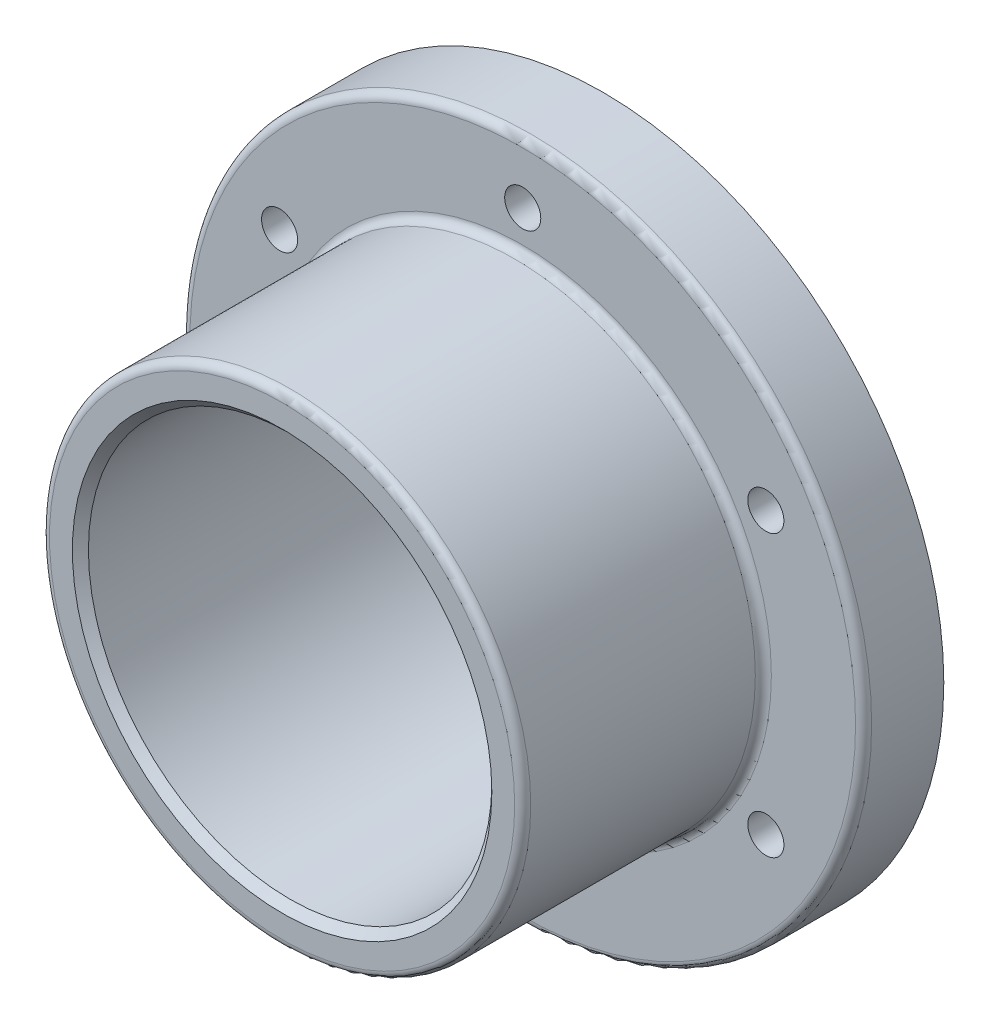
SolidWorks part; units mm, degrees
ref_plane "Front Plane" through (0, 0, 0) normal (0, 0, 1) x (1, 0, 0)
ref_plane "Top Plane" through (0, 0, 0) normal (0, 1, 0) x (1, 0, 0)
ref_plane "Right Plane" through (0, 0, 0) normal (1, 0, 0) x (0, 0, -1)
sketch "Sketch1" plane through (0, 0, 0) normal (0, 0, 1) x (1, 0, 0)
  circle A0 centre (0, 0) radius 42.5
  dimension "D1" = 85
extrude "Boss-Extrude1" add sketch "Sketch1" along normal blind 10
sketch "Sketch2" plane through (0, 0, 10) normal (0, 0, 1) x (1, 0, 0)
  circle A0 centre (0, 0) radius 30
  dimension "D1" = 60
extrude "Boss-Extrude2" add sketch "Sketch2" along normal blind 30
sketch "Sketch3" plane through (0, 0, 40) normal (0, 0, 1) x (1, 0, 0)
  circle A0 centre (0, 0) radius 25.15
  dimension "D1" = 50.3
extrude "Cut-Extrude1" cut sketch "Sketch3" against normal through all
chamfer "Chamfer1" distance 1 angle 45 2 edges at (25.15, 0, 40) (25.15, 0, 0)
fillet "Fillet1" radius 1 3 edges at (30, 0, 10) (42.5, 0, 10) (30, 0, 40)
sketch "Sketch4" plane through (0, 0, 10) normal (0, 0, 1) x (1, 0, 0)
  line L0 (0, 0) -> (0, 42.0295) construction
  circle A0 centre (0, 35) radius 2.25
  dimension "D1" = 4.5
  dimension "D2" = 35
extrude "Cut-Extrude2" cut sketch "Sketch4" against normal through all
pattern_circular "CirPattern1" count 6 over 360 about axis through (0, 0, 0) along (0, 0, 1) of "Cut-Extrude2"
